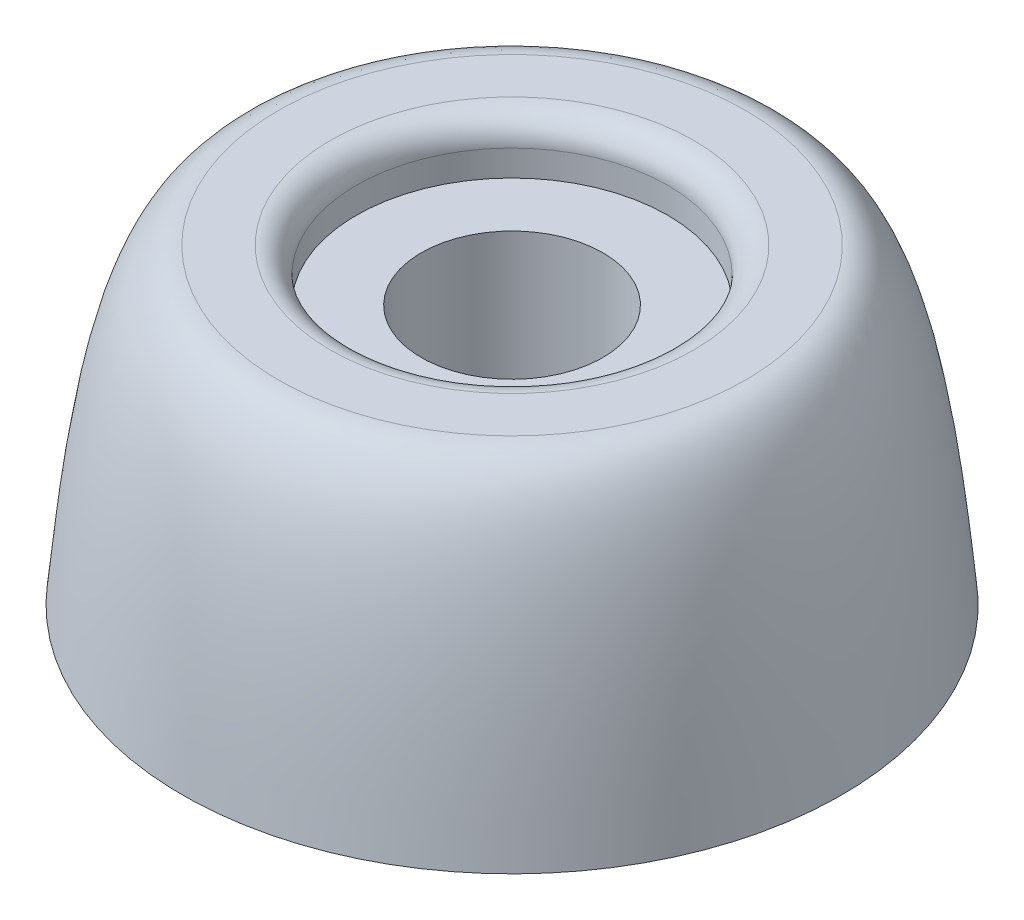
SolidWorks part; units mm, degrees
ref_plane "Front Plane" through (0, 0, 0) normal (0, 0, 1) x (1, 0, 0)
ref_plane "Top Plane" through (0, 0, 0) normal (0, 1, 0) x (1, 0, 0)
ref_plane "Right Plane" through (0, 0, 0) normal (1, 0, 0) x (0, 0, -1)
sketch "Sketch1" plane through (0, 0, 0) normal (0, 0, 1) x (1, 0, 0)
  line L0 (0, 0) -> (0, 10)
  line L1 (0, 10) -> (-6, 10)
  line L2 (-12.7, 0) -> (0, 0)
  line L3 (0, 10) -> (-3.5, 10)
  line L4 (0, 10) -> (0, 0)
  line L5 (0, 0) -> (-3.5, 0)
  line L6 (-3.5, 10) -> (-3.5, 0)
  line L7 (-6, 10) -> (-6, 12)
  line L8 (-6, 12) -> (-9, 12)
  spline S0 degree 3 poles (-9, 12) (-11.62, 11.9725) (-12.2945, 4.0578) (-12.7, 0) knots 0 0 0 0 1 1 1 1
  point P7 (0, 0)
  dimension "D1" = 10
  dimension "D2" = 12.7
  dimension "D3" = 3.5
  dimension "D4" = 6
  dimension "D5" = 2
  dimension "D6" = 3
revolve "Revolve1" add sketch "Sketch1" angle 360 about L0
fillet "Fillet1" radius 1 1 edges at (0, 12, -6)
